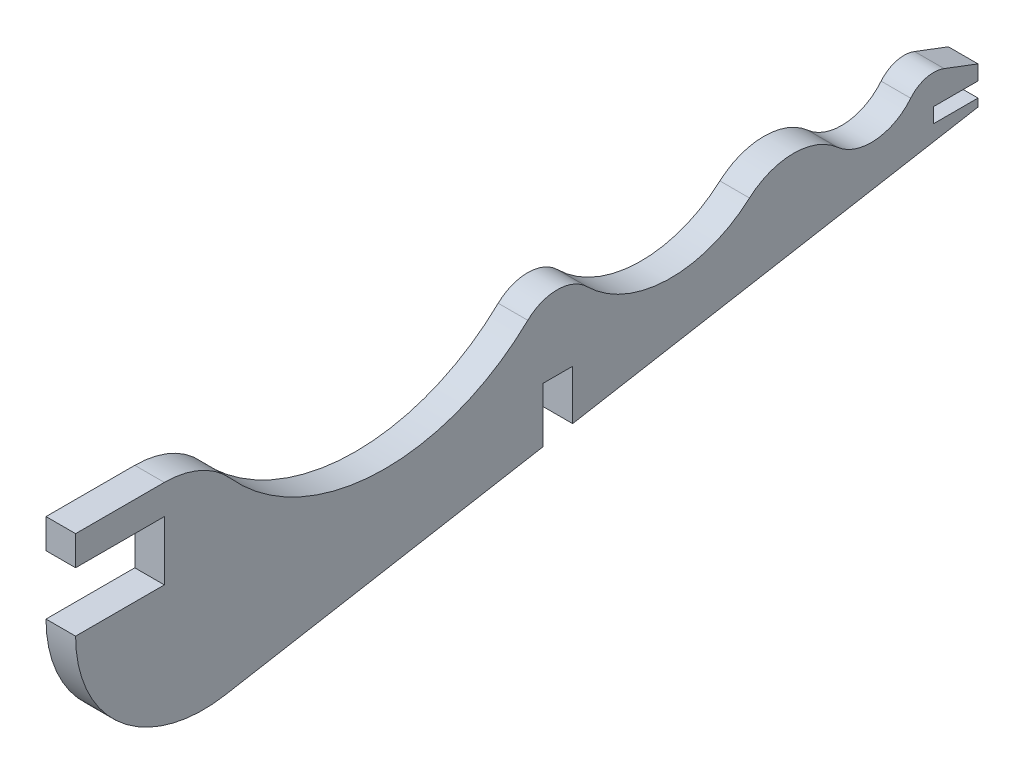
SolidWorks part; units mm, degrees
ref_plane "Front Plane" through (0, 0, 0) normal (0, 0, 1) x (1, 0, 0)
ref_plane "Top Plane" through (0, 0, 0) normal (0, 1, 0) x (1, 0, 0)
ref_plane "Right Plane" through (0, 0, 0) normal (1, 0, 0) x (0, 0, -1)
sketch "Sketch1" plane through (0, 0, 0) normal (1, 0, 0) x (0, 0, -1)
  line L0 (0, 0) -> (-9.525, 0) construction
  line L1 (-19.05, 0) -> (-19.05, 3.175)
  line L2 (-19.05, 3.175) -> (0, 3.175)
  line L3 (0, 3.175) -> (0, 9.525)
  line L4 (0, 9.525) -> (-19.05, 9.525)
  line L8 (-19.05, 28.6665) -> (-19.05, -18.1684) construction
  line L9 (-203.2, 156.9731) -> (-203.2, -3.175) construction
  line L10 (-19.05, 9.525) -> (-203.2, 9.525) construction
  line L11 (-203.2, 9.525) -> (-203.2, 15.875)
  line L12 (-203.2, 15.875) -> (-184.15, 15.875)
  line L13 (-203.2, 9.525) -> (-184.15, 9.525)
  line L14 (-184.15, 9.525) -> (-184.15, -3.175)
  line L15 (-184.15, -3.175) -> (-203.2, -3.175)
  line L18 (0, 0) -> (-203.2, -54.4473) construction
  line L19 (-41.8156, 3.175) -> (-26.1058, 3.175) construction
  line L22 (-32.4325, 3.175) -> (-203.2, -11.7652) construction
  line L23 (0, 0) -> (-19.05, -3.359) construction
  line L26 (-36.911, -6.5084) -> (-171.0415, -30.1592) construction
  line L27 (-9.525, 0) -> (-19.05, 0)
  line L29 (-9.525, 0) -> (-9.525, -1.6795)
  line L30 (-9.525, -1.6795) -> (-171.0415, -30.1592)
  line L31 (-203.2, -3.175) -> (-203.2, -1058.8441) construction
  arc A0 (-23.9687, 7.1911) -> (-19.05, 9.525) centre (-19.05, 3.175) cw
  arc A2 (-93.4135, 6.8801) -> (-106.1478, 7.0006) centre (-99.8426, 0.3887) ccw
  arc A3 (-106.1478, 7.0006) -> (-169.9448, 9.525) centre (-136.8233, 39.1691) cw
  arc A4 (-169.9448, 9.525) -> (-184.15, 15.875) centre (-184.15, -3.1889) ccw
  arc A5 (-58.5652, 5.9384) -> (-39.6931, 5.9361) centre (-49.1304, -4.6777) cw
  arc A6 (-39.6931, 5.9361) -> (-23.9687, 7.1911) centre (-32.4325, 14.1017) ccw
  arc A7 (-58.5652, 5.9384) -> (-93.4135, 6.8801) centre (-75.4875, 24.9797) cw
  arc A8 (-203.2, -3.175) -> (-171.0415, -30.1592) centre (-175.7995, -3.175) ccw
  point P40 (0, 0)
  dimension "D10" = 44.45
  dimension "D12" = 6.35
  dimension "D13" = 6.35
  dimension "D15" = 5
  dimension "D1" = 19.05
  dimension "D2" = 19.05
  dimension "D3" = 3.175
  dimension "D4" = 6.35
  dimension "D5" = 19.05
  dimension "D6" = 184.15
  dimension "D7" = 6.35
  dimension "D8" = 19.05
  dimension "D9" = 19.05
  dimension "D11" = 15
  dimension "D14" = 5
  dimension "D16" = 12.7
extrude "Boss-Extrude1" add sketch "Sketch1" along normal blind 6.35
sketch "Sketch2" plane through (6.35, 0, 0) normal (1, 0, 0) x (0, 0, -1)
  line L0 (-184.15, 3.175) -> (-19.05, 3.175) construction
  line L1 (-110.7422, 3.175) -> (-110.7422, -19.5268) construction
  line L2 (-171.0415, -30.1592) -> (-9.525, -1.6795) construction
  line L3 (-88.6591, -19.5268) -> (-88.6591, 3.175) construction
  line L4 (-110.7422, -19.5268) -> (-88.6591, -19.5268) construction
  line L5 (-99.7007, -19.5268) -> (-99.7007, -12.2449) construction
  line L6 (-99.7007, -6.35) -> (-99.7007, 3.175) construction
  line L7 (-96.5257, -6.35) -> (-102.8757, -6.35)
  line L8 (-96.5257, -6.35) -> (-96.5257, -18.1398)
  line L9 (-96.5257, -18.1398) -> (-102.8757, -18.1398)
  line L10 (-102.8757, -6.35) -> (-102.8757, -18.1398)
  line L11 (-96.5257, -6.35) -> (-102.8757, -18.1398) construction
  line L12 (-96.5257, -18.1398) -> (-102.8757, -6.35) construction
  line L13 (-184.15, 9.525) -> (-184.15, -3.175) construction
  arc A0 (-169.9448, 9.525) -> (-106.1478, 7.0006) centre (-136.8233, 39.1691) ccw construction
  arc A1 (-93.4135, 6.8801) -> (-58.5652, 5.9384) centre (-75.4875, 24.9797) ccw construction
  point P24 (0, 0)
  dimension "D1" = 6.35
  dimension "D2" = 9.525
extrude "Cut-Extrude1" cut sketch "Sketch2" against normal through all
sketch "Sketch3" plane through (6.35, 0, 0) normal (1, 0, 0) x (0, 0, -1)
  line L0 (-9.525, 3.175) -> (-9.525, 6.35)
  line L1 (-19.05, 3.175) -> (0, 3.175) construction
  line L2 (-9.525, 6.35) -> (-9.525, 9.525) construction
  line L3 (0, 9.525) -> (-19.05, 9.525) construction
  line L4 (-16.7954, 9.1113) -> (-9.525, 6.35)
  line L5 (-19.05, 9.525) -> (0, 9.525)
  line L6 (0, 9.525) -> (0, 3.175)
  line L7 (0, 3.175) -> (-9.525, 3.175)
  arc A0 (-19.05, 9.525) -> (-16.7954, 9.1113) centre (-19.05, 3.175) cw
  arc A1 (-19.05, 9.525) -> (-23.9687, 7.1911) centre (-19.05, 3.175) ccw construction
  dimension "D1" = 6.35
extrude "Cut-Extrude2" cut sketch "Sketch3" against normal through all
